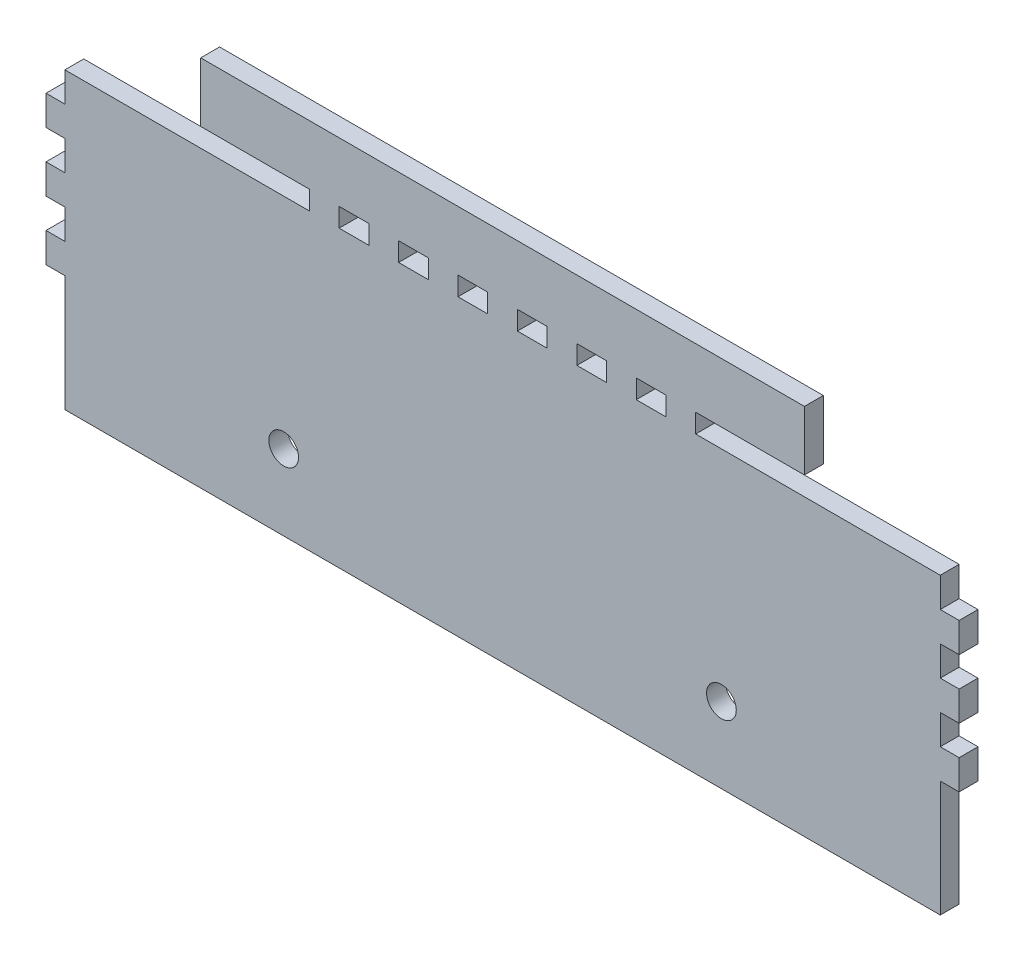
SolidWorks part; units mm, degrees
ref_plane "Front Plane" through (0, 0, 0) normal (0, 0, 1) x (1, 0, 0)
ref_plane "Top Plane" through (0, 0, 0) normal (0, 1, 0) x (1, 0, 0)
ref_plane "Right Plane" through (0, 0, 0) normal (1, 0, 0) x (0, 0, -1)
sketch "Sketch1" plane through (0, 0, 0) normal (0, 0, 1) x (1, 0, 0)
  line L0 (-147.32, -36.83) -> (0, -36.83) construction
  line L1 (-147.32, 0) -> (-106.16, 0)
  line L2 (0, 0) -> (0, -5)
  line L3 (0, -49.53) -> (-147.32, -49.53)
  line L4 (-147.32, 0) -> (-147.32, -5)
  line L5 (-101.16, 3.175) -> (-96.16, 3.175)
  line L6 (-124.46, 13.175) -> (-22.86, 13.175)
  line L7 (-51.16, 0) -> (-46.16, 0)
  line L8 (-46.16, 0) -> (-46.16, 3.175)
  line L9 (-124.46, 13.175) -> (-124.46, 3.175)
  line L10 (-22.86, 13.175) -> (-22.86, 3.175)
  line L11 (-124.46, 3.175) -> (-106.16, 3.175)
  line L13 (-91.16, 3.175) -> (-86.16, 3.175)
  line L14 (-81.16, 3.175) -> (-76.16, 3.175)
  line L15 (-71.16, 3.175) -> (-66.16, 3.175)
  line L16 (-106.16, 0) -> (-106.16, 3.175)
  line L17 (-61.16, 3.175) -> (-56.16, 3.175)
  line L18 (-101.16, 0) -> (-101.16, 3.175)
  line L19 (-101.16, 0) -> (-96.16, 0)
  line L20 (-96.16, 0) -> (-96.16, 3.175)
  line L21 (-51.16, 3.175) -> (-46.16, 3.175)
  line L22 (-91.16, 0) -> (-91.16, 3.175)
  line L23 (-91.16, 0) -> (-86.16, 0)
  line L24 (-86.16, 0) -> (-86.16, 3.175)
  line L25 (-41.16, 3.175) -> (-22.86, 3.175)
  line L26 (-81.16, 0) -> (-81.16, 3.175)
  line L27 (-81.16, 0) -> (-76.16, 0)
  line L28 (-76.16, 0) -> (-76.16, 3.175)
  line L30 (-71.16, 0) -> (-71.16, 3.175)
  line L31 (-71.16, 0) -> (-66.16, 0)
  line L32 (-66.16, 0) -> (-66.16, 3.175)
  line L34 (-61.16, 0) -> (-61.16, 3.175)
  line L35 (-61.16, 0) -> (-56.16, 0)
  line L36 (-56.16, 0) -> (-56.16, 3.175)
  line L38 (-51.16, 0) -> (-51.16, 3.175)
  line L39 (-41.16, 3.175) -> (-41.16, 0)
  line L40 (-41.16, 0) -> (0, 0)
  line L44 (-147.32, -10) -> (-147.32, -15)
  line L45 (-147.32, -5) -> (-150.495, -5)
  line L47 (-147.32, -15) -> (-150.495, -15)
  line L48 (-147.32, -10) -> (-150.495, -10)
  line L49 (-150.495, -5) -> (-150.495, -10)
  line L50 (-150.495, -15) -> (-150.495, -20)
  line L51 (-147.32, -20) -> (-150.495, -20)
  line L52 (-147.32, -20) -> (-147.32, -25)
  line L53 (-147.32, -25) -> (-150.495, -25)
  line L54 (-150.495, -25) -> (-150.495, -30)
  line L55 (-147.32, -30) -> (-150.495, -30)
  line L56 (-147.32, -30) -> (-147.32, -49.53)
  line L59 (-73.66, 4.592) -> (-73.66, -103.652) construction
  line L60 (3.175, -25) -> (3.175, -30)
  line L61 (3.175, -15) -> (3.175, -20)
  line L62 (3.175, -5) -> (3.175, -10)
  line L63 (3.175, -5) -> (0, -5)
  line L64 (3.175, -10) -> (0, -10)
  line L65 (3.175, -15) -> (0, -15)
  line L66 (3.175, -20) -> (0, -20)
  line L67 (3.175, -25) -> (0, -25)
  line L68 (3.175, -30) -> (0, -30)
  line L69 (0, -20) -> (0, -25)
  line L70 (0, -30) -> (0, -49.53)
  line L71 (0, -10) -> (0, -15)
  circle A0 centre (-110.49, -36.83) radius 2.5
  circle A1 centre (-36.83, -36.83) radius 2.5
  point P72 (-73.66, -49.53)
  dimension "D3" = 36.83
  dimension "D5" = 12.7
  dimension "D6" = 3.175
  dimension "D1" = 5
  dimension "D2" = 73.66
  dimension "D4" = 36.83
  dimension "D7" = 36.83
  dimension "D9" = 5
  dimension "D10" = 5
  dimension "D12" = 5
  dimension "D13" = 101.6
  dimension "D8" = 3.175
  dimension "D14" = 10
  dimension "D15" = 5
  dimension "D16" = 5
  dimension "D17" = 5
  dimension "D18" = 5
  dimension "D19" = 5
  dimension "D20" = 5
  dimension "D21" = 5
  dimension "D11" = 3
extrude "Boss-Extrude1" add sketch "Sketch1" along normal blind 3.175
sketch "Sketch2" plane through (0, 0, 3.175) normal (0, 0, 1) x (1, 0, 0)
